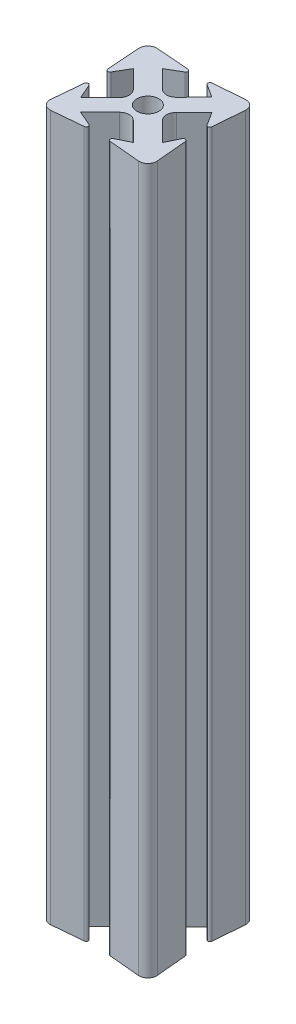
SolidWorks part; units mm, degrees
ref_plane "Front Plane" through (0, 0, 0) normal (0, 0, 1) x (1, 0, 0)
ref_plane "Top Plane" through (0, 0, 0) normal (0, 1, 0) x (1, 0, 0)
ref_plane "Right Plane" through (0, 0, 0) normal (1, 0, 0) x (0, 0, -1)
sketch "Sketch1" plane through (0, 0, 0) normal (0, 1, 0) x (1, 0, 0)
  line L1 (-16.2586, 10.8064) -> (9.1414, 10.8064)
  line L2 (-16.2586, 10.8064) -> (-16.2586, -14.5936)
  line L3 (-16.2586, -14.5936) -> (9.1414, -14.5936)
  line L4 (9.1414, 10.8064) -> (9.1414, -14.5936)
  dimension "D1" = 25.4
  dimension "D2" = 25.4
sketch "Sketch2" plane through (0, 0, 0) normal (0, 1, 0) x (1, 0, 0)
  line L0 (-19.5248, -1.8936) -> (12.956, -1.8936)
  line L1 (-3.2844, -16.3317) -> (-3.2844, 12.7118)
  line L2 (-16.2586, -14.5936) -> (9.1414, 10.8064)
  line L3 (-16.2586, 10.8064) -> (9.1414, -14.5936)
  line L4 (-16.2586, -14.5936) -> (-15.2113, -2.9758)
  line L5 (-15.2113, -2.9758) -> (-12.9014, -8.3163)
  line L6 (-12.9014, -8.3163) -> (2.3702, 7.1647)
  line L8 (-1.9815, 9.9398) -> (9.1414, 10.8064)
  line L9 (-16.2586, -14.5936) -> (-4.6409, -13.5463)
  line L10 (-4.6409, -13.5463) -> (-9.9814, -11.2364)
  line L11 (-9.9814, -11.2364) -> (5.4997, 4.0353)
  line L12 (5.4997, 4.0353) -> (8.2747, -0.3164)
  line L13 (8.2747, -0.3164) -> (9.1414, 10.8064)
  line L14 (-15.392, -0.9626) -> (-12.6169, 3.7508)
  line L15 (-12.6169, 3.7508) -> (2.3702, -11.2364)
  line L16 (-15.392, -0.9626) -> (-16.2586, 10.8064)
  line L17 (2.3702, -11.2364) -> (-2.3468, -13.5463)
  line L18 (-2.3468, -13.5463) -> (9.1414, -14.5936)
  line L19 (5.7842, -7.8224) -> (8.0941, -3.1054)
  line L20 (-4.4895, 9.9398) -> (-9.203, 7.1647)
  line L21 (-9.203, 7.1647) -> (5.7842, -7.8224)
  line L22 (-4.4895, 9.9398) -> (-16.2586, 10.8064)
  line L23 (8.0941, -3.1054) -> (9.1414, -14.5936)
  line L24 (2.3702, 7.1647) -> (-1.9815, 9.9398)
extrude "Boss-Extrude1" add sketch "Sketch2" along normal blind 603.25 contours L20 L22 L3 L6 L21 | L16 L14 L15 L6 L3 | L2 L21 L0 L11 L12 L13 | L1 L21 L2 L8 L24 L6 | L15 L0 L6 L5 L4 L2 | L6 L15 L0 L3 | L21 L6 L3 L2 L1 | L0 L15 L2 | L2 L15 L11 L1 L3 | L21 L0 L1 L3 L11 | L21 L1 L2 | L21 L2 L1 L0 | L6 L21 L1 | L1 L11 L3 | L0 L21 L11 | L15 L6 L0 | L2 L0 L1 | L0 L3 L1 | L23 L19 L21 L11 L3 | L17 L18 L3 L11 L1 L15 | L15 L2 L9 L10 L11
sketch "Sketch8" plane through (0, 603.25, 0) normal (0, 1, 0) x (1, 0, 0)
  circle A0 centre (-3.527, -1.9152) radius 2.5653
extrude "Cut-Extrude4" cut sketch "Sketch8" against normal blind 604.996
fillet "Fillet1" radius 2.032 4 edges at (9.1414, 301.625, 14.5936) (-16.2586, 301.625, 14.5936) (9.1414, 301.625, -10.8064) (-16.2586, 301.625, -10.8064)
fillet "Fillet2" radius 0.508 8 edges at (8.0941, 301.625, 3.1054) (-2.3468, 301.625, 13.5463) (-4.6409, 301.625, 13.5463) (-15.392, 301.625, 0.9626) (-15.2113, 301.625, 2.9758) (-4.4895, 301.625, -9.9398) (-1.9815, 301.625, -9.9398) (8.2747, 301.625, 0.3164)
sketch "Sketch5" plane through (-0.7818, 0, -10.0333) normal (-0.0777, 0, -0.997) x (-0.997, 0, 0.0777)
  line L1 (-3.8674, 570.4548) -> (8.7883, 570.4548)
  line L2 (-3.8674, 570.4548) -> (-3.8674, 294.9774)
  line L3 (-3.8674, 294.9774) -> (8.7883, 294.9774)
  line L4 (8.7883, 570.4548) -> (8.7883, 294.9774)
extrude "Boss-Extrude3" add sketch "Sketch5" along normal blind 4.572 contours L2 L1 L4 L3
sketch "Sketch6" plane through (-1.1369, 0, -14.5914) normal (-0.0777, 0, -0.997) x (-0.997, 0, 0.0777)
  line L0 (2.4604, 570.4548) -> (2.4604, 387.4972)
  line L1 (-3.8674, 570.4548) -> (8.7883, 570.4548) construction
  circle A0 centre (2.4604, 545.2326) radius 4.6177
  circle A1 centre (2.4604, 513.8542) radius 4.5036
  circle A2 centre (2.4604, 479.2551) radius 4.6219
  circle A3 centre (2.4604, 446.3016) radius 4.6727
  circle A4 centre (2.4604, 414.3422) radius 4.616
extrude "Cut-Extrude2" cut sketch "Sketch6" against normal blind 4.572 contours A4 | A3 | A2 | A1 | A0
sketch "Sketch7" plane through (-1.1369, 0, -14.5914) normal (-0.0777, 0, -0.997) x (-0.997, 0, 0.0777)
  circle A0 centre (2.6102, 377.3779) radius 4.5449
  circle A1 centre (2.1574, 338.1358) radius 4.6727
extrude "Cut-Extrude3" cut sketch "Sketch7" against normal blind 4.572 contours A1 | A0
fillet "Fillet3" radius 2.286 4 edges at (-0.3263, 301.625, 1.7119) (-3.377, 301.625, -1.3387) (-6.7677, 301.625, 2.0985) (-3.7635, 301.625, 5.1026)
sketch "Sketch9" plane through (-14.8226, 0, -1.3362) normal (-0.996, 0, -0.0898) x (-0.0898, 0, 0.996)
  line L1 (34.8752, 621.0678) -> (-25.5256, 621.0678)
  line L2 (34.8752, 621.0678) -> (34.8752, 244.3633)
  line L3 (34.8752, 244.3633) -> (-25.5256, 244.3633)
  line L4 (-25.5256, 621.0678) -> (-25.5256, 244.3633)
extrude "Cut-Extrude6" cut sketch "Sketch9" against normal blind 38.354 and the other way blind 10.922
sketch "Sketch10" plane through (7.7466, 0, -0.7062) normal (0.9959, 0, -0.0908) x (-0.0908, 0, -0.9959)
  line L1 (-33.4565, 165.1747) -> (24.2491, 165.1747)
  line L2 (-33.4565, 165.1747) -> (-33.4565, 251.8534)
  line L3 (-33.4565, 251.8534) -> (24.2491, 251.8534)
  line L4 (24.2491, 165.1747) -> (24.2491, 251.8534)
extrude "Cut-Extrude7" cut sketch "Sketch10" against normal blind 33.274 and the other way blind 11.938
